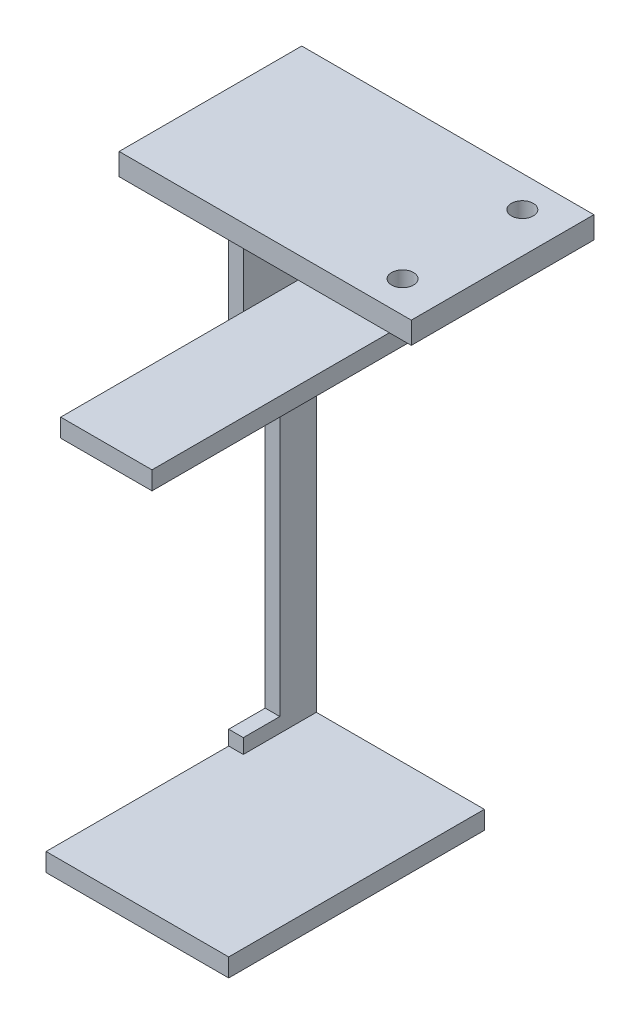
SolidWorks part; units mm, degrees
ref_plane "Front Plane" through (0, 0, 0) normal (0, 0, 1) x (1, 0, 0)
ref_plane "Top Plane" through (0, 0, 0) normal (0, 1, 0) x (1, 0, 0)
ref_plane "Right Plane" through (0, 0, 0) normal (1, 0, 0) x (0, 0, -1)
sketch "Sketch1" plane through (0, 0, 0) normal (0, 1, 0) x (1, 0, 0)
  line L0 (-5.5, 22.2) -> (-1.2476, 22.2) construction
  line L1 (0, 0) -> (-40, 0)
  line L2 (0, 0) -> (0, 25)
  line L3 (0, 25) -> (-40, 25)
  line L4 (-40, 0) -> (-40, 25)
  line L5 (-5.5, 2.8) -> (-1.0181, 2.8) construction
  line L6 (0, 12.5) -> (-40, 12.5) construction
  line L7 (-4, 20.7) -> (-4, 23.8751) construction
  circle A0 centre (-5.5, 20.7) radius 1.5
  circle A1 centre (-5.5, 4.3) radius 1.5
  dimension "D3" = 3
  dimension "D1" = 40
  dimension "D2" = 25
  dimension "D4" = 19.4
  dimension "D5" = 4
extrude "Boss-Extrude1" add sketch "Sketch1" along normal blind 3
sketch "Sketch2" plane through (0, 0, 0) normal (0, -1, 0) x (1, 0, 0)
  line L1 (-40, -25) -> (-38, -25)
  line L2 (-40, -25) -> (-40, -15)
  line L3 (-40, -15) -> (-38, -15)
  line L4 (-38, -25) -> (-38, -15)
  dimension "D1" = 2
  dimension "D2" = 10
extrude "Boss-Extrude2" add sketch "Sketch2" along normal blind 75
sketch "Sketch6" plane through (0, -75, 0) normal (0, -1, 0) x (1, 0, 0)
  line L1 (-40, -25) -> (-15, -25)
  line L2 (-40, -25) -> (-40, 10)
  line L3 (-40, 10) -> (-15, 10)
  line L4 (-15, -25) -> (-15, 10)
  dimension "D1" = 25
  dimension "D2" = 35
extrude "Boss-Extrude3" add sketch "Sketch6" along normal blind 2.5
sketch "Sketch7" plane through (-38, 0, 0) normal (1, 0, 0) x (0, 0, -1)
  line L0 (25, -75) -> (25, 0) construction
  line L1 (25, -25) -> (-10, -25)
  line L2 (25, -25) -> (25, -22.5)
  line L3 (25, -22.5) -> (-10, -22.5)
  line L4 (-10, -25) -> (-10, -22.5)
  line L5 (-10, -77.5) -> (-10, -75) construction
  line L6 (25, -75) -> (-10, -75) construction
  dimension "D1" = 2.5
  dimension "D2" = 50
extrude "Boss-Extrude4" add sketch "Sketch7" along normal blind 12.5
sketch "Sketch8" plane through (-38, 0, 0) normal (1, 0, 0) x (0, 0, -1)
  line L0 (15, -27) -> (20, -27)
  line L1 (15, -75) -> (15, -25) construction
  line L2 (20, -27) -> (20, -73)
  line L3 (20, -73) -> (15, -73)
  line L4 (25, -75) -> (15, -75) construction
  line L5 (-10, -25) -> (25, -25) construction
  line L6 (25, -75) -> (25, -25) construction
  line L7 (15, -27) -> (15, -73)
  dimension "D1" = 2
  dimension "D2" = 2
  dimension "D3" = 5
extrude "Cut-Extrude2" cut sketch "Sketch8" against normal through all
